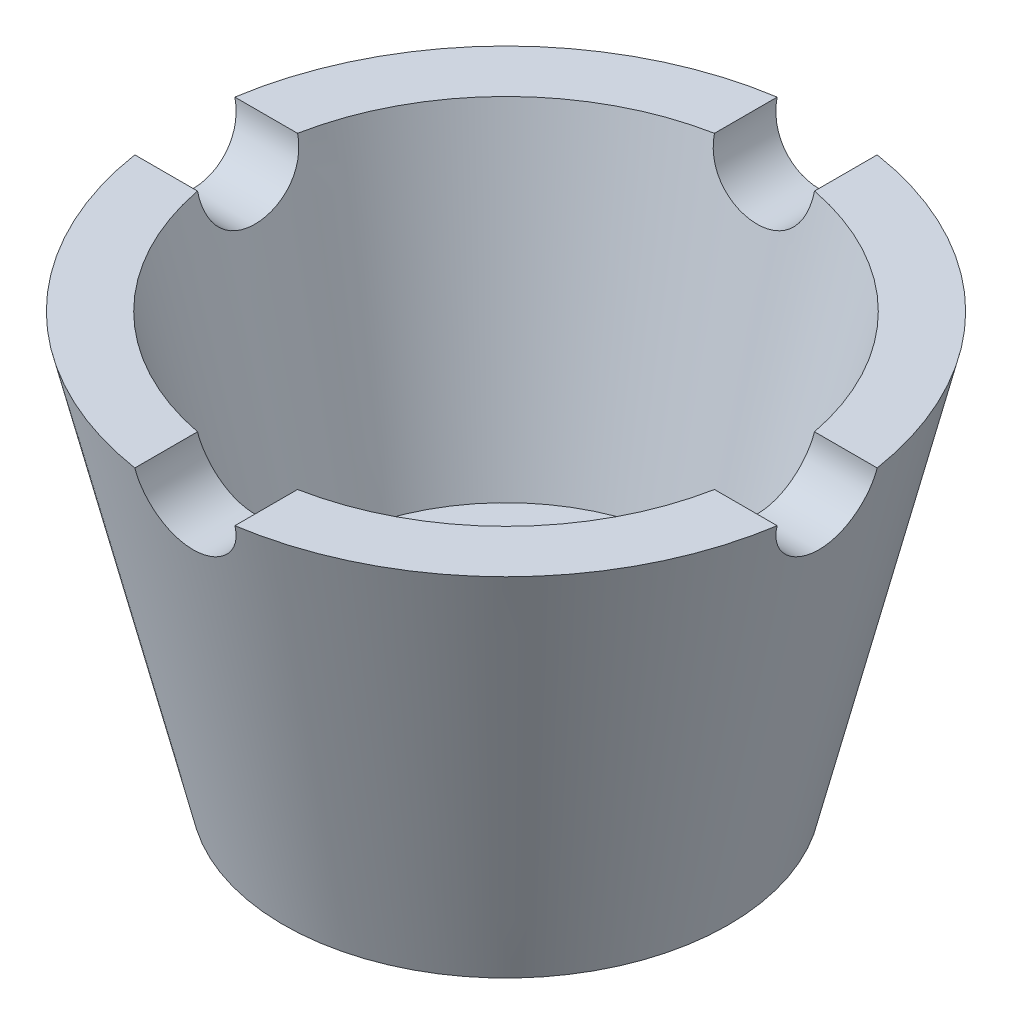
SolidWorks part; units mm, degrees
ref_plane "Front Plane" through (0, 0, 0) normal (0, 0, 1) x (1, 0, 0)
ref_plane "Top Plane" through (0, 0, 0) normal (0, 1, 0) x (1, 0, 0)
ref_plane "Right Plane" through (0, 0, 0) normal (1, 0, 0) x (0, 0, -1)
sketch "Sketch2" plane through (0, 0, 0) normal (0, 0, 1) x (1, 0, 0)
  line L0 (0, 0) -> (0, 42) construction
  line L1 (11.25, 0) -> (11.25, 12)
  line L2 (11.25, 12) -> (19, 12)
  line L3 (19, 12) -> (26.3238, 42)
  line L4 (26.3238, 42) -> (32.5, 42)
  line L5 (32.5, 42) -> (22.2467, 0)
  line L6 (22.2467, 0) -> (11.25, 0)
  point P5 (0, 0)
  dimension "D1" = 42
  dimension "D2" = 12
  dimension "D3" = 6
  dimension "D4" = 19
  dimension "D5" = 32.5
  dimension "D6" = 11.25
revolve "Revolve1" add sketch "Sketch2" angle 360 about L0
sketch "Sketch3" plane through (0, 0, 0) normal (0, 0, 1) x (1, 0, 0)
  line L0 (26.3238, 42) -> (-26.3238, 42) construction
  circle A0 centre (0, 42) radius 5
  dimension "D1" = 10
extrude "Cut-Extrude1" cut sketch "Sketch3" against normal through all both and the other way through all
pattern_circular "CirPattern1" count 4 over 360 about axis through (0, 0, 0) along (0, -1, 0) of "Cut-Extrude1"
